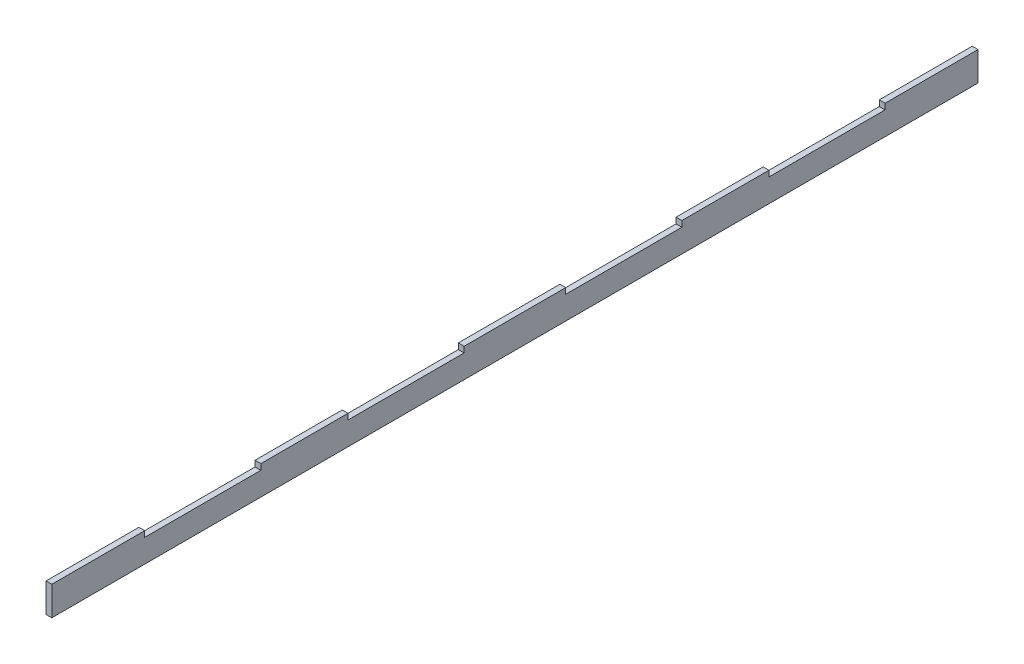
SolidWorks part; units mm, degrees
material "ABS PC"
ref_plane "Front Plane" through (0, 0, 0) normal (0, 0, 1) x (1, 0, 0)
ref_plane "Top Plane" through (0, 0, 0) normal (0, 1, 0) x (1, 0, 0)
ref_plane "Right Plane" through (0, 0, 0) normal (1, 0, 0) x (0, 0, -1)
sketch "Sketch1" plane through (0, 0, 0) normal (1, 0, 0) x (0, 0, -1)
  line L1 (-159.5, -5) -> (159.5, -5)
  line L2 (-159.5, -5) -> (-159.5, 5)
  line L3 (-159.5, 5) -> (159.5, 5)
  line L4 (159.5, -5) -> (159.5, 5)
  line L5 (-159.5, -5) -> (159.5, 5) construction
  line L6 (-159.5, 5) -> (159.5, -5) construction
  point P0 (0, 0)
  dimension "D1" = 10
  dimension "D2" = 319
extrude "Boss-Extrude1" add sketch "Sketch1" along normal blind 2
sketch "Sketch2" plane through (2, 0, 0) normal (1, 0, 0) x (0, 0, -1)
  line L0 (159.5, 5) -> (-159.5, 5) construction
  line L1 (-127.5, 5) -> (-87.5, 5)
  line L2 (-127.5, 5) -> (-127.5, 3)
  line L3 (-127.5, 3) -> (-87.5, 3)
  line L4 (-87.5, 5) -> (-87.5, 3)
  line L5 (-159.5, 5) -> (-159.5, -5) construction
  line L6 (-57.5, 5) -> (-17.5, 5)
  line L7 (-57.5, 5) -> (-57.5, 3)
  line L8 (-57.5, 3) -> (-17.5, 3)
  line L9 (-17.5, 5) -> (-17.5, 3)
  line L10 (0, 55) -> (0, -55) construction
  line L11 (17.5, 5) -> (17.5, 3)
  line L12 (57.5, 5) -> (17.5, 5)
  line L13 (57.5, 5) -> (57.5, 3)
  line L14 (57.5, 3) -> (17.5, 3)
  line L15 (127.5, 5) -> (127.5, 3)
  line L16 (127.5, 5) -> (87.5, 5)
  line L17 (87.5, 5) -> (87.5, 3)
  line L18 (127.5, 3) -> (87.5, 3)
  dimension "D1" = 32
  dimension "D2" = 2
  dimension "D3" = 40
  dimension "D4" = 30
  dimension "D5" = 40
  dimension "D6" = 2
extrude "Cut-Extrude1" cut sketch "Sketch2" against normal through all both and the other way through all
